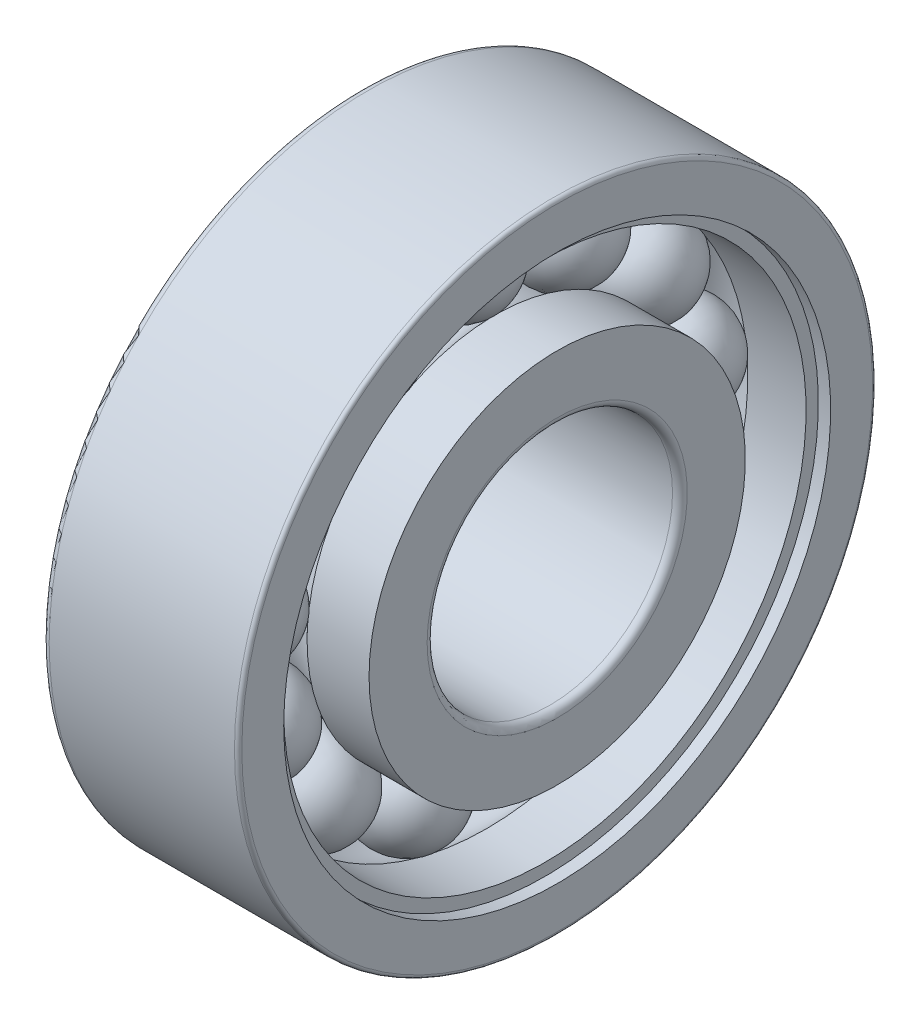
SolidWorks part; units mm, degrees
ref_plane "Front" through (0, 0, 0) normal (0, 0, 1) x (1, 0, 0)
ref_plane "Top" through (0, 0, 0) normal (0, 1, 0) x (1, 0, 0)
ref_plane "Right" through (0, 0, 0) normal (1, 0, 0) x (0, 0, -1)
sketch "Sketch1" plane through (0, 0, 0) normal (0, 0, 1) x (1, 0, 0)
  line L0 (-3.0919, 0) -> (2.899, 0) construction
  line L1 (-3.0919, 9) -> (2.899, 9) construction
  line L2 (-2, 9) -> (2, 9)
  arc A0 (-2, 9) -> (2, 9) centre (0, 9) ccw
  dimension "R" = 2
  dimension "D1" = 9
revolve "Revolve1" add sketch "Sketch1" angle 360 about L1
sketch "Sketch2" plane through (0, 0, 0) normal (0, 0, 1) x (1, 0, 0)
  line L0 (-4, 7.6667) -> (-1.4773, 7.6667)
  line L1 (4, 7.6667) -> (4, 5)
  line L2 (4, 5) -> (-4, 5)
  line L3 (-4, 5) -> (-4, 7.6667)
  line L4 (-2.9924, 0) -> (3.9982, 0) construction
  line L5 (-1.8743, 9) -> (3.1755, 9) construction
  line L7 (1.4773, 7.6667) -> (4, 7.6667)
  line L8 (-4, 6.2861) -> (-4, 1.454) construction
  arc A0 (-1.4773, 7.6667) -> (1.4773, 7.6667) centre (0, 9) ccw
  dimension "D1" = 9
  dimension "B" = 8
  dimension "D2" = 1.99
  dimension "d" = 10
  dimension "D3" = 15.3333
  dimension "T" = 8
  dimension "D6" = 4
revolve "Revolve2" add sketch "Sketch2" angle 360 about L4
sketch "Sketch3" plane through (0, 0, 0) normal (0, 0, 1) x (1, 0, 0)
  line L0 (-4, 10.3333) -> (-4, 13)
  line L1 (-4, 13) -> (4, 13)
  line L2 (4, 13) -> (4, 11.1433)
  line L3 (3.5, 10.6433) -> (1.1223, 10.6433)
  line L4 (-2.9924, 0) -> (3.4329, 0) construction
  line L6 (-1.7375, 9) -> (2.2712, 9) construction
  line L7 (-1.4773, 10.3333) -> (-4, 10.3333)
  line L8 (3.5, 10.6433) -> (3.5, 11.1433)
  line L9 (3.5, 11.1433) -> (4, 11.1433)
  arc A0 (1.1223, 10.6433) -> (-1.4773, 10.3333) centre (0, 9) ccw
  dimension "D1" = 9
  dimension "D4" = 1.99
  dimension "B" = 8
  dimension "DD" = 26
  dimension "D3" = 21.2867
  dimension "D5" = 20.6667
  dimension "D6" = 0.5
  dimension "D7" = 0.5
  dimension "D2" = 4
revolve "Revolve3" add sketch "Sketch3" angle 360 about L4
pattern_circular "Circular-Pattern1" count 13 over 360 about axis through (0, 0, 0) along (1, 0, 0) of "Revolve1"
fillet "Fillet1" radius 0.3 2 edges at (4, 0, 5) (-4, 0, 13)
fillet "Fillet2" radius 0.15 2 edges at (4, 0, 13) (-4, 0, 5)
equation "\"R@Sketch1\" =  ( \"DD@Sketch3\" - \"d@Sketch2\" )  / 8"
equation "\"D1@Sketch1\"=(\"d@Sketch2\"+\"DD@Sketch3\")/4"
equation "\"D1@Sketch2\"=(\"d@Sketch2\"+\"DD@Sketch3\")/4"
equation "\"D3@Sketch2\" =  \"d@Sketch2\"+  ( \"DD@Sketch3\" - \"d@Sketch2\" )  /3"
equation "\"D2@Sketch2\" =  ( \"DD@Sketch3\" - \"d@Sketch2\" )  / 8 - 0.01"
equation "\"D6@Sketch2\" = \"B@Sketch2\" / 2"
equation "\"B@Sketch3\" = \"B@Sketch2\""
equation "\"D2@Sketch3\" = \"B@Sketch3\" / 2"
equation "\"D1@Sketch3\"=(\"d@Sketch2\"+\"DD@Sketch3\")/4"
equation "\"D3@Sketch3\" = (  \"DD@Sketch3\" -  (\"DD@Sketch3\" - \"d@Sketch2\"  )  / 3 )  * 1.03"
equation "\"D5@Sketch3\" = \"DD@Sketch3\" -  (  \"DD@Sketch3\" - \"d@Sketch2\")  / 3"
equation "\"D6@Sketch3\" = \"d@Sketch2\" / 20"
equation "\"D7@Sketch3\"=\"D6@Sketch3\""
equation "\"D4@Sketch3\"=(\"DD@Sketch3\"-\"d@Sketch2\")/8-0.01"
equation "\"m@Circular-Pattern1\" = int( 3.14159265 / atn(\"R@Sketch1\" / sqr((\"d@Sketch2\"+\"DD@Sketch3\")/4 * (\"d@Sketch2\"+\"DD@Sketch3\")/4 - \"R@Sketch1\" *  \"R@Sketch1\")))-1"
